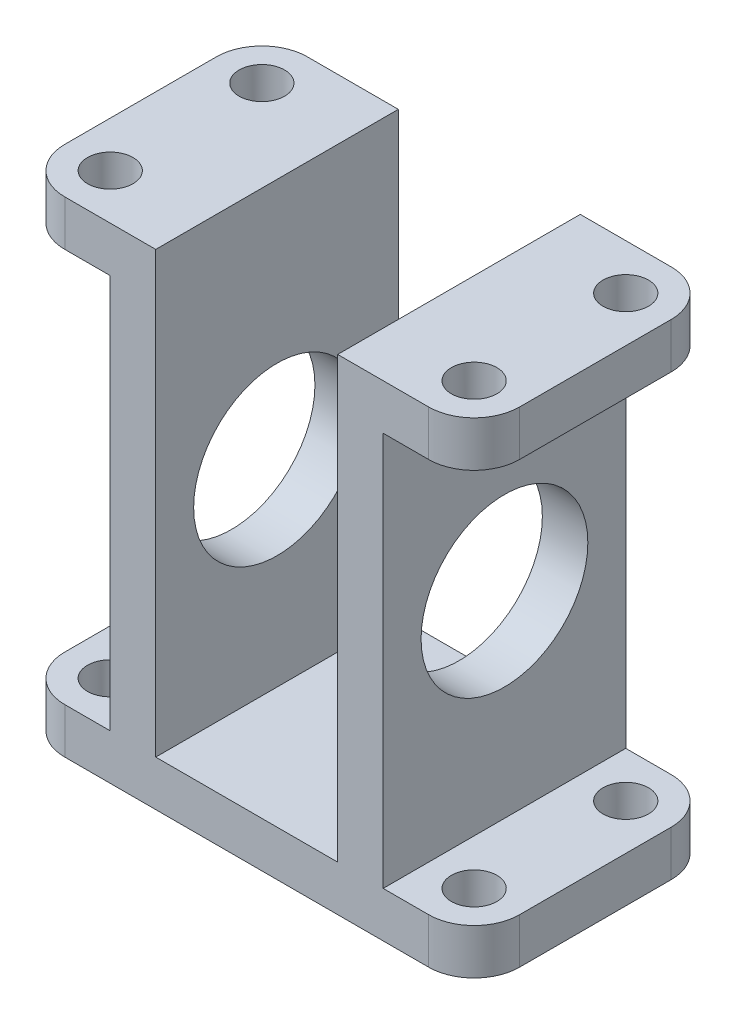
SolidWorks part; units mm, degrees
material "6061 合金"
ref_plane "前视基准面" through (0, 0, 0) normal (0, 0, 1) x (1, 0, 0)
ref_plane "上视基准面" through (0, 0, 0) normal (0, 1, 0) x (1, 0, 0)
ref_plane "右视基准面" through (0, 0, 0) normal (1, 0, 0) x (0, 0, -1)
sketch "草图1" plane through (0, 0, 0) normal (0, 1, 0) x (1, 0, 0)
  line L1 (-15, -8) -> (15, -8)
  line L2 (-15, -8) -> (-15, 8)
  line L3 (-15, 8) -> (15, 8)
  line L4 (15, -8) -> (15, 8)
  line L5 (-15, -8) -> (15, 8) construction
  line L6 (-15, 8) -> (15, -8) construction
  point P0 (0, 0)
  dimension "D1" = 30
  dimension "D2" = 16
extrude "凸台-拉伸1" add sketch "草图1" along normal blind 3
sketch "草图2" plane through (0, 3, 0) normal (0, 1, 0) x (1, 0, 0)
  line L0 (0, 8) -> (0, -8) construction
  line L1 (15, 8) -> (-15, 8) construction
  line L2 (-15, -8) -> (15, -8) construction
  line L3 (9, -8) -> (6, -8)
  line L4 (-9, 8) -> (-6, 8)
  line L5 (-9, 8) -> (-9, -8)
  line L6 (-9, -8) -> (-6, -8)
  line L7 (-6, 8) -> (-6, -8)
  line L8 (6, 8) -> (6, -8)
  line L9 (9, 8) -> (6, 8)
  line L10 (9, 8) -> (9, -8)
  dimension "D1" = 3
  dimension "D2" = 6
extrude "凸台-拉伸2" add sketch "草图2" along normal blind 29
sketch "草图4" plane through (-9, 0, 0) normal (-1, 0, 0) x (0, 0, 1)
  line L0 (8, 32) -> (8, 3) construction
  line L1 (-8, 32) -> (8, 32)
  line L2 (-8, 32) -> (-8, 29)
  line L3 (-8, 29) -> (8, 29)
  line L4 (8, 32) -> (8, 29)
  dimension "D1" = 3
extrude "凸台-拉伸3" add sketch "草图4" along normal blind 6
sketch "草图5" plane through (9, 0, 0) normal (1, 0, 0) x (0, 0, -1)
  line L0 (8, 32) -> (8, 3) construction
  line L1 (-8, 32) -> (8, 32)
  line L2 (-8, 32) -> (-8, 29)
  line L3 (-8, 29) -> (8, 29)
  line L4 (8, 32) -> (8, 29)
  dimension "D1" = 3
extrude "凸台-拉伸4" add sketch "草图5" along normal blind 6
sketch "草图6" plane through (9, 0, 0) normal (1, 0, 0) x (0, 0, -1)
  line L0 (0, 0) -> (0, 32) construction
  line L1 (8, 32) -> (-8, 32) construction
  line L2 (-8, 16) -> (8, 16) construction
  line L3 (-8, 29) -> (-8, 3) construction
  line L4 (8, 29) -> (8, 3) construction
  circle A0 centre (0, 16) radius 5.5
  dimension "D1" = 11
extrude "切除-拉伸1" cut sketch "草图6" against normal through all
sketch "草图7" plane through (0, 32, 0) normal (0, 1, 0) x (1, 0, 0)
  line L0 (0, 8) -> (0, -8) construction
  line L1 (6, 8) -> (-6, 8) construction
  line L2 (-6, -8) -> (6, -8) construction
  line L3 (-15, 0) -> (15, 0) construction
  line L4 (-15, -8) -> (-15, 8) construction
  line L5 (15, 8) -> (15, -8) construction
  line L6 (15, 8) -> (6, 8) construction
  circle A0 centre (12, 5) radius 1.5
  circle A2 centre (12, -5) radius 1.5
  circle A3 centre (-12, -5) radius 1.5
  circle A4 centre (-12, 5) radius 1.5
  dimension "D1" = 3
  dimension "D3" = 3
  dimension "D2" = 3
extrude "切除-拉伸2" cut sketch "草图7" against normal through all
fillet "圆角1" radius 3 8 edges at (15, 1.5, -8) (15, 1.5, 8) (15, 30.5, 8) (15, 30.5, -8) (-15, 30.5, -8) (-15, 30.5, 8) (-15, 1.5, 8) (-15, 1.5, -8)
